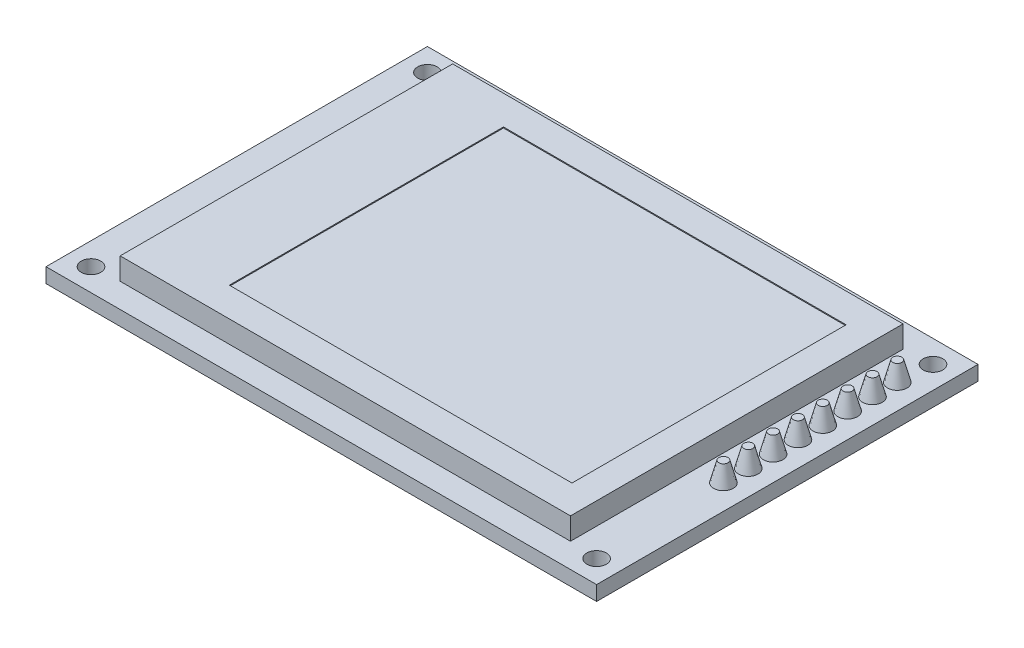
SolidWorks part; units mm, degrees
ref_plane "Спереди" through (0, 0, 0) normal (0, 0, 1) x (1, 0, 0)
ref_plane "Сверху" through (0, 0, 0) normal (0, 1, 0) x (1, 0, 0)
ref_plane "Справа" through (0, 0, 0) normal (1, 0, 0) x (0, 0, -1)
sketch "Эскиз1" plane through (0, 0, 0) normal (0, 1, 0) x (1, 0, 0)
  line L0 (-17.52, 12.495) -> (17.52, -15.535) construction
  line L5 (-17.52, 12.495) -> (17.52, 12.495) construction
  line L6 (-17.52, 12.495) -> (-17.52, -15.535) construction
  line L7 (-17.52, -15.535) -> (17.52, -15.535) construction
  line L8 (17.52, 12.495) -> (17.52, -15.535) construction
  line L9 (17.52, 12.495) -> (-17.52, -15.535) construction
  line L10 (-17.52, -1.52) -> (17.52, -1.52) construction
  line L11 (-30.78, 17.98) -> (25.52, 17.98)
  line L12 (-30.78, 17.98) -> (-30.78, -21.02)
  line L13 (-30.78, -21.02) -> (25.52, -21.02)
  line L14 (25.52, 17.98) -> (25.52, -21.02)
  line L15 (-30.78, 17.98) -> (25.52, -21.02) construction
  line L16 (25.52, 17.98) -> (-30.78, -21.02) construction
  line L17 (0, 0) -> (0, -1.52) construction
  line L18 (23.22, -18.72) -> (-28.48, -18.72) construction
  line L19 (23.22, -18.72) -> (23.22, 15.68) construction
  line L20 (23.22, 15.68) -> (-28.48, 15.68) construction
  line L21 (-28.48, -18.72) -> (-28.48, 15.68) construction
  line L22 (23.22, -18.72) -> (-28.48, 15.68) construction
  line L23 (23.22, 15.68) -> (-28.48, -18.72) construction
  line L24 (20.35, -18.52) -> (-25.698, -18.52) construction
  line L25 (20.35, -18.52) -> (20.35, 15.48) construction
  line L26 (20.35, 15.48) -> (-25.698, 15.48) construction
  line L27 (-25.698, -18.52) -> (-25.698, 15.48) construction
  line L28 (20.35, -18.52) -> (-25.698, 15.48) construction
  line L29 (20.35, 15.48) -> (-25.698, -18.52) construction
  circle A0 centre (-28.48, 15.68) radius 1
  circle A1 centre (-28.48, 15.68) radius 2.5 construction
  circle A2 centre (23.22, 15.68) radius 1
  circle A3 centre (23.22, 15.68) radius 2.5 construction
  circle A4 centre (-28.48, -18.72) radius 1
  circle A5 centre (-28.48, -18.72) radius 2.5 construction
  circle A6 centre (23.22, -18.72) radius 1
  circle A7 centre (23.22, -18.72) radius 2.5 construction
  point P11 (25.52, -1.52)
  point P12 (-2.63, -1.52)
  point P25 (-2.674, -1.52)
  dimension "D6" = 2
  dimension "D7" = 5
  dimension "D1" = 56.3
  dimension "D2" = 39
  dimension "D3" = 8
  dimension "D4" = 34.4
  dimension "D5" = 51.7
  dimension "D8" = 2.83
  dimension "D9" = 34
  dimension "D10" = 1.52
  dimension "D11" = 28.03
  dimension "D12" = 35.04
extrude "Бобышка-Вытянуть1" add sketch "Эскиз1" along normal blind 1.5
sketch "Эскиз2" plane through (0, 1.5, 0) normal (0, 1, 0) x (1, 0, 0)
  line L0 (-17.52, 12.495) -> (17.52, -15.535) construction
  line L1 (-17.52, 12.495) -> (17.52, 12.495) construction
  line L2 (-17.52, 12.495) -> (-17.52, -15.535) construction
  line L3 (-17.52, -15.535) -> (17.52, -15.535) construction
  line L4 (17.52, 12.495) -> (17.52, -15.535) construction
  line L5 (17.52, 12.495) -> (-17.52, -15.535) construction
  line L6 (-17.52, -1.52) -> (17.52, -1.52) construction
  line L11 (-25.698, -18.52) -> (20.35, -18.52)
  line L13 (0, 0) -> (0, -1.52) construction
  line L21 (20.35, -18.52) -> (20.35, 15.48)
  line L22 (20.35, 15.48) -> (-25.698, 15.48)
  line L23 (-25.698, -18.52) -> (-25.698, 15.48)
  line L25 (20.35, 15.48) -> (-25.698, -18.52) construction
  point P11 (-2.63, -1.52)
  point P24 (-2.674, -1.52)
  dimension "D2" = 46.048
  dimension "D3" = 34
  dimension "D10" = 1.52
extrude "Бобышка-Вытянуть2" add sketch "Эскиз2" along normal blind 2.25
sketch "Эскиз3" plane through (0, 3.75, 0) normal (0, 1, 0) x (1, 0, 0)
  line L0 (-17.52, 12.495) -> (17.52, -15.535) construction
  line L1 (-17.52, 12.495) -> (17.52, 12.495)
  line L2 (-17.52, 12.495) -> (-17.52, -15.535)
  line L3 (-17.52, -15.535) -> (17.52, -15.535)
  line L4 (17.52, 12.495) -> (17.52, -15.535)
  line L5 (17.52, 12.495) -> (-17.52, -15.535) construction
  line L6 (-17.52, -1.52) -> (17.52, -1.52) construction
  line L13 (0, 0) -> (0, -1.52) construction
  point P13 (-2.63, -1.52)
  point P26 (-2.674, -1.52)
  dimension "D3" = 28.03
  dimension "D9" = 1.52
  dimension "D11" = 35.04
extrude "Вырез-Вытянуть1" cut sketch "Эскиз3" against normal blind 0.1
sketch "Эскиз5" plane through (0, 1.5, 0) normal (0, 1, 0) x (1, 0, 0)
  line L0 (23.22, 15.68) -> (23.22, -18.72) construction
  line L1 (23.22, 15.68) -> (22.99, 15.68) construction
  line L2 (22.99, 15.68) -> (22.99, 12.26) construction
  circle A1 centre (22.99, 12.26) radius 1
  circle A3 centre (22.99, 9.72) radius 1
  circle A5 centre (22.99, 7.18) radius 1
  circle A7 centre (22.99, 4.64) radius 1
  circle A8 centre (22.99, 2.1) radius 1
  circle A9 centre (22.99, -0.44) radius 1
  circle A10 centre (22.99, -2.98) radius 1
  circle A11 centre (22.99, -5.52) radius 1
  dimension "D3" = 2
  dimension "D1" = 0.23
  dimension "D2" = 3.42
  dimension "D4" = 8
extrude "Бобышка-Вытянуть4" add sketch "Эскиз5" along normal blind 2 draft 15
sketch "Эскиз6" plane through (0, 3.65, 0) normal (0, 1, 0) x (1, 0, 0)
  line L0 (9.1491, 48.4649) -> (115.8158, 48.4649) construction
